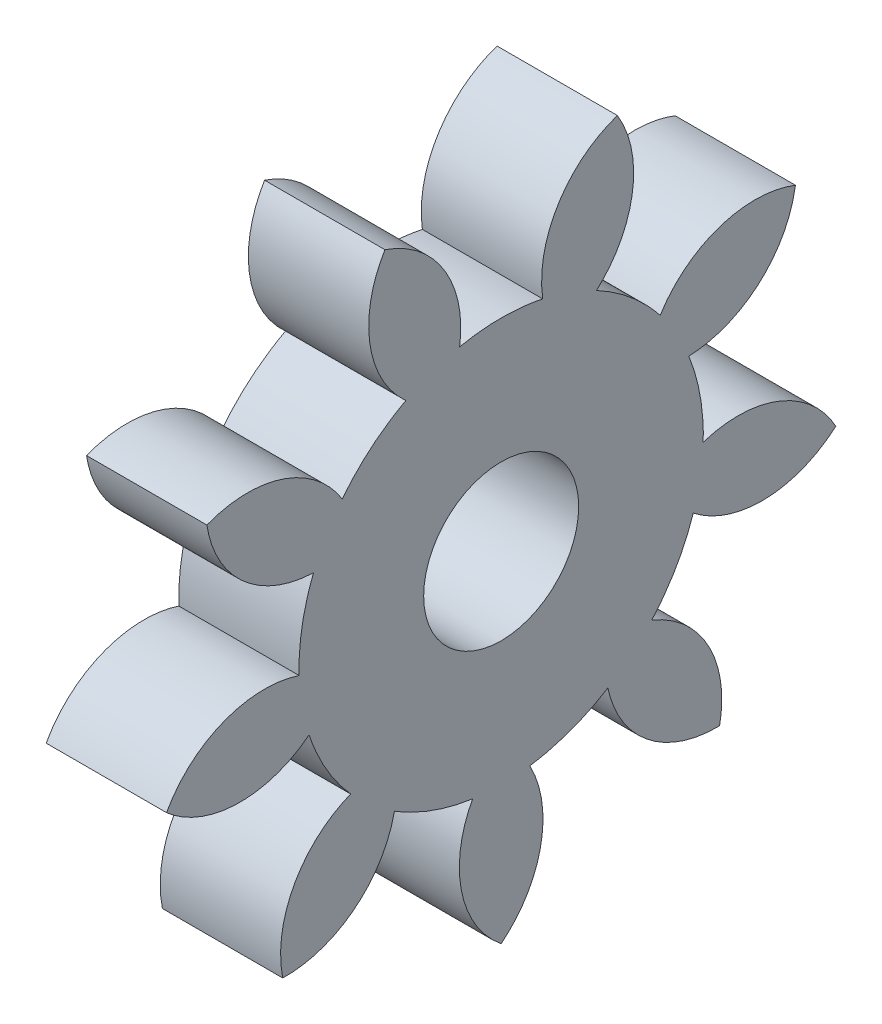
SolidWorks part; units mm, degrees
ref_plane "Plane1" through (0, 0, 0) normal (0, 0, 1) x (1, 0, 0)
ref_plane "Plane2" through (0, 0, 0) normal (0, 1, 0) x (1, 0, 0)
ref_plane "Plane3" through (0, 0, 0) normal (1, 0, 0) x (0, 0, -1)
sketch "HoldingSke" plane through (0, 0, 0) normal (0, 1, 0) x (1, 0, 0)
  line L0 (0, 0) -> (500.2823, -88.2133)
  line L1 (-15, 0) -> (100, 0) construction
  line L2 (0, 0) -> (-2.1039, 2.3779)
  line L3 (0, 0) -> (-11.863, 4.5341)
  line L4 (0, 0) -> (8.5048, 1.4996)
  line L5 (0, 0) -> (-47.5972, -17.7524)
  line L6 (0, 0) -> (-2.632, -1.7758)
  line L7 (-2.1039, 2.3779) -> (8.8308, 51.9871)
  line L8 (-76.2, 54.61) -> (-72.771, 54.61)
  line L9 (-71.009, 38.7566) -> (-53.1078, 45.2721)
  line L10 (-76.2, 71.12) -> (104.1128, 71.12)
  line L11 (0, 0) -> (-3.175, 0)
  line L12 (-76.2, 101.6) -> (-76.1492, 101.6)
  line L13 (24.9733, 27.94) -> (52.9518, 28.4284)
  line L14 (24.9733, 27.94) -> (25.0241, 27.9398)
  line L15 (24.9733, 27.94) -> (100.4021, 29.52)
  circle A0 centre (0, 0) radius 1.5875
  circle A1 centre (0, 0) radius 4.1402
  circle A2 centre (0, 0) radius 38.1
  circle A3 centre (0, 0) radius 1.5875
  dimension "MHD" = 8.2804
  dimension "Hub_dia" = 76.2
  dimension "Bore" = 3.175
  dimension "MBD" = 3.175
  dimension "Num_teeth" = 10
  dimension "Pitch_radius" = 180.3128
  dimension "Pitch" = 508
  dimension "Width" = 3.175
  dimension "Overall_len" = 50.8
  dimension "Show_teeth" = 10
  dimension "Thickness" = 3.175
  dimension "OAL" = 50.8001
  dimension "T_dim" = 3.429
  dimension "Ap" = 20
  dimension "H" = 19.05
  dimension "Backlash" = 0.0508
  dimension "Addendum_fac" = 1
  dimension "Dedendum_fac" = 1.2
  dimension "Clearance_fac" = 0.2
  dimension "Dedendum_add" = 0.0508
sketch "BasProSke" plane through (0, 0, 0) normal (0, 1, 0) x (1, 0, 0)
  line L0 (-10, 0) -> (60, 0) construction
  line L1 (0, 0) -> (0, 6.985)
  line L2 (0, 0) -> (3.175, 0)
  line L3 (3.175, 0) -> (3.175, 6.985)
  line L4 (3.175, 6.985) -> (0, 6.985)
  dimension "Diameter" = 13.97
  dimension "Thickness" = 3.175
revolve "Base-Revolve" add sketch "BasProSke" angle 360 about L0
sketch "TooCutSke" plane through (0, 0, 0) normal (1, 0, 0) x (0, 0, -1)
  line L1 (0, 0) -> (0, 107) construction
  line L2 (0, 0) -> (-1.1786, 5.5922) construction
  line L3 (0, 0) -> (-3.8703, 10.6336) construction
  line L4 (-1.1786, 5.5922) -> (-1.9352, 5.3168) construction
  arc A0 (0.8509, 4.0518) -> (-0.8509, 4.0518) centre (0, 0) ccw
  arc A1 (2.4581, 6.5653) -> (-2.4581, 6.5653) centre (0, 0) ccw
  circle A2 centre (0, 0) radius 5.715 construction
  circle A3 centre (0, 0) radius 5.3703 construction
  arc A4 (-0.8509, 4.0518) -> (-2.4581, 6.5653) centre (-3.1139, 4.3754) ccw
  arc A5 (2.4581, 6.5653) -> (0.8509, 4.0518) centre (3.1139, 4.3754) ccw
  dimension "Root_dia" = 8.2804
  dimension "Overcut_dia" = 14.0208
  dimension "Pitch_dia" = 11.43
  dimension "Base_dia" = 10.7407
  dimension "Flank_rad" = 2.286
  dimension "Half_ang" = 20
  dimension "Half_CT" = 0.8051
extrude "ToothCut" cut sketch "TooCutSke" along normal through all
fillet "Breaks" [suppressed] radius 0.0254
fillet "RootFillets" [suppressed] radius 0.3048
pattern_circular "TeethCuts" count 10 every 40 about axis through (-10, 0, 0) along (1, 0, 0) of "ToothCut"
sketch "HubNeaOneSke" plane through (0, 0, 0) normal (-1, 0, 0) x (0, 0, 1)
  circle A0 centre (0, 0) radius 4.1402
  dimension "Diameter" = 8.2804
extrude "HubNearOne" [suppressed] add sketch "HubNeaOneSke" along normal blind 47.6251
sketch "HubNeaBotSke" plane through (0, 0, 0) normal (-1, 0, 0) x (0, 0, 1)
  circle A0 centre (0, 0) radius 4.1402
  dimension "Diameter" = 8.2804
extrude "HubNearBoth" [suppressed] add sketch "HubNeaBotSke" along normal blind 23.8125
ref_plane "FarPln" through (3.175, 0, 0) normal (1, 0, 0) x (0, 0, -1)
sketch "HubFarSke" plane through (3.175, 0, 0) normal (1, 0, 0) x (0, 0, -1)
  circle A0 centre (0, 0) radius 4.1402
  dimension "Diameter" = 8.2804
extrude "HubFar" [suppressed] add sketch "HubFarSke" along normal blind 23.8125
sketch "BorSke" plane through (0, 0, 0) normal (1, 0, 0) x (0, 0, -1)
  circle A0 centre (0, 0) radius 1.5875
  dimension "Diameter" = 3.175
extrude "Bore" cut sketch "BorSke" along normal mid plane 101.6001
sketch "KeySke" plane through (0, 0, 0) normal (1, 0, 0) x (0, 0, -1)
  line L0 (-0.127, 0) -> (-0.127, 1.8415)
  line L1 (-0.127, 1.8415) -> (0.127, 1.8415)
  line L2 (0.127, 1.8415) -> (0.127, 0)
  line L3 (0, 0) -> (0, 34) construction
  line L4 (-0.127, 0) -> (0.127, 0)
  dimension "Offset" = 1.8415
  dimension "Width" = 0.254
extrude "Keyway" [suppressed] cut sketch "KeySke" along normal mid plane 101.6001
pattern_circular "Keyway2" [suppressed] count 2 every 90 about axis through (-10, 0, 0) along (1, 0, 0)
scale "Scale1" scale about centroid uniform scaling no x scale factor 1 y scale factor 1.288 z scale factor 1.288
equation "' \"Pitch@HoldingSke\" = 4"
equation "' \"Num_teeth@HoldingSke\" = 12"
equation "' \"Ap@HoldingSke\" =  20"
equation "' \"Width@HoldingSke\" = 0.5"
equation "' \"Hub_dia@HoldingSke\"= 1"
equation "' \"Overall_len@HoldingSke\" = 1.0"
equation "' \"Bore@HoldingSke\" = 0.75"
equation "' \"T_dim@HoldingSke\" = 0.85"
equation "' \"Width@KeySke\" = 0.25"
equation "' \"Show_teeth@HoldingSke\" = 13"
equation "' \"Backlash@HoldingSke\" = 0.009"
equation "' \"Addendum_fac@HoldingSke\" = 1.0"
equation "' \"Dedendum_fac@HoldingSke\" = 1.25"
equation "' \"Dedendum_add@HoldingSke\" = 0.00005"
equation "' \"Clearance_fac@HoldingSke\" = 0.25"
equation "' \"Pitch@HoldingSke\" = 0.5"
equation "' \"Num_teeth@HoldingSke\" = 23"
equation "' \"Show_teeth@HoldingSke\" = 23"
equation "' \"Backlash@HoldingSke\" = 0.0375"
equation "\"Overcut_dia@TooCutSke\"=(9 + 2 * \"Addendum_fac@HoldingSke\") / \"Pitch@HoldingSke\" + 0.002"
equation "\"Pitch_dia@TooCutSke\"=9/ \"Pitch@HoldingSke\""
equation "\"Base_dia@TooCutSke\"=9 / \"Pitch@HoldingSke\" * cos((\"Ap@HoldingSke\"  * 3.14159265 / 180))"
equation "\"Root_dia@TooCutSke\"=(9 + 2) / \"Pitch@HoldingSke\" - 2 * (\"Addendum_fac@HoldingSke\" + \"Dedendum_fac@HoldingSke\") / \"Pitch@HoldingSke\" - \"Dedendum_add@HoldingSke\" * 2"
equation "\"Half_ang@TooCutSke\"=180 / 9"
equation "\"Half_CT@TooCutSke\"=9 / \"Pitch@HoldingSke\" * sin((3.14159265 / 2 / \"Num_teeth@HoldingSke\")) / 2 - 7 * \"Backlash@HoldingSke\" / 4"
equation "\"Flank_rad@TooCutSke\"=9/ \"Pitch@HoldingSke\" / 5"
equation "\"Radius@RootFillets\" = \"Clearance_fac@HoldingSke\" / \"Pitch@HoldingSke\" + \"Dedendum_add@HoldingSke\""
equation "\"Break_rad@Breaks\" = 0.02 / \"Pitch@HoldingSke\""
equation "\"Thickness@HoldingSke\" = \"Width@HoldingSke\""
equation "\"OAL@HoldingSke\" = \"Thickness@HoldingSke\""
equation "\"MHD@HoldingSke\" = (\"Num_teeth@HoldingSke\" + 2) / \"Pitch@HoldingSke\" - 2 * (\"Addendum_fac@HoldingSke\" + \"Dedendum_fac@HoldingSke\")  / \"Pitch@HoldingSke\" - \"Dedendum_add@HoldingSke\" * 2"
equation "\"MBD@HoldingSke\" = (\"Num_teeth@HoldingSke\" + 2) / \"Pitch@HoldingSke\" - 2 * (\"Addendum_fac@HoldingSke\" + \"Dedendum_fac@HoldingSke\")  / \"Pitch@HoldingSke\" - \"Dedendum_add@HoldingSke\" * 2 - 0.002"
equation "\"MHD@HoldingSke\" = ((sgn( \"MHD@HoldingSke\" - \"Hub_dia@HoldingSke\" )-1)*( \"MHD@HoldingSke\" - \"Hub_dia@HoldingSke\" ))/-2+ \"Hub_dia@HoldingSke\""
equation "\"MBD@HoldingSke\" = ((sgn( \"MBD@HoldingSke\" - \"Bore@HoldingSke\" )-1)*( \"MBD@HoldingSke\" - \"Bore@HoldingSke\" ))/-2+ \"Bore@HoldingSke\""
equation "\"OAL@HoldingSke\" = ((sgn( \"OAL@HoldingSke\" - \"Overall_len@HoldingSke\" )+1)*( \"OAL@HoldingSke\" - \"Overall_len@HoldingSke\" ))/2 + \"Overall_len@HoldingSke\" + 0.000002"
equation "\"Num_teeth@TeethCuts\"=int( 9 ) + 1"
equation "\"Num_teeth@TeethCuts\" = ((sgn( \"Num_teeth@TeethCuts\" - \"Num_teeth@HoldingSke\" )-1)*( \"Num_teeth@TeethCuts\" - \"Num_teeth@HoldingSke\" ))/-2+ \"Num_teeth@HoldingSke\""
equation "\"Num_teeth@TeethCuts\" = ((sgn( \"Num_teeth@TeethCuts\" - 2.0)+1)*( \"Num_teeth@TeethCuts\" - 2.0))/2 +2.0"
equation "\"Angle@TeethCuts\"=360.0 / 9"
equation "\"Diameter@BasProSke\"=(9 + 2 * \"Addendum_fac@HoldingSke\") / \"Pitch@HoldingSke\""
equation "\"Thickness@BasProSke\"  = \"Thickness@HoldingSke\""
equation "' \"Fillet_rad@BasProSke\" =  \"Thickness@HoldingSke\" * 0.05"
equation "\"MHD@HoldingSke\" = ((sgn( \"MHD@HoldingSke\" - \"Root_dia@TooCutSke\" )-1)*( \"MHD@HoldingSke\" - \"Root_dia@TooCutSke\" ))/-2+ \"Root_dia@TooCutSke\""
equation "\"Diameter@HubNeaOneSke\" = \"MHD@HoldingSke\""
equation "\"Length@HubNearOne\" = \"OAL@HoldingSke\" - \"Thickness@BasProSke\""
equation "\"Diameter@HubNeaBotSke\" = \"MHD@HoldingSke\""
equation "\"Length@HubNearBoth\" = ( \"OAL@HoldingSke\" - \"Thickness@BasProSke\" ) / 2.0"
equation "\"Thickness@FarPln\" = \"Thickness@BasProSke\""
equation "\"Diameter@HubFarSke\" = \"MHD@HoldingSke\""
equation "\"Length@HubFar\" = ( \"OAL@HoldingSke\" - \"Thickness@BasProSke\" ) / 2.0"
equation "\"Diameter@BorSke\" = \"MBD@HoldingSke\""
equation "\"D1@Bore\" = \"OAL@HoldingSke\" * 2.0"
equation "\"D1@Keyway\" = \"OAL@HoldingSke\" * 2.0"
equation "\"Offset@KeySke\" = \"T_dim@HoldingSke\" - \"MBD@HoldingSke\" / 2.0"
